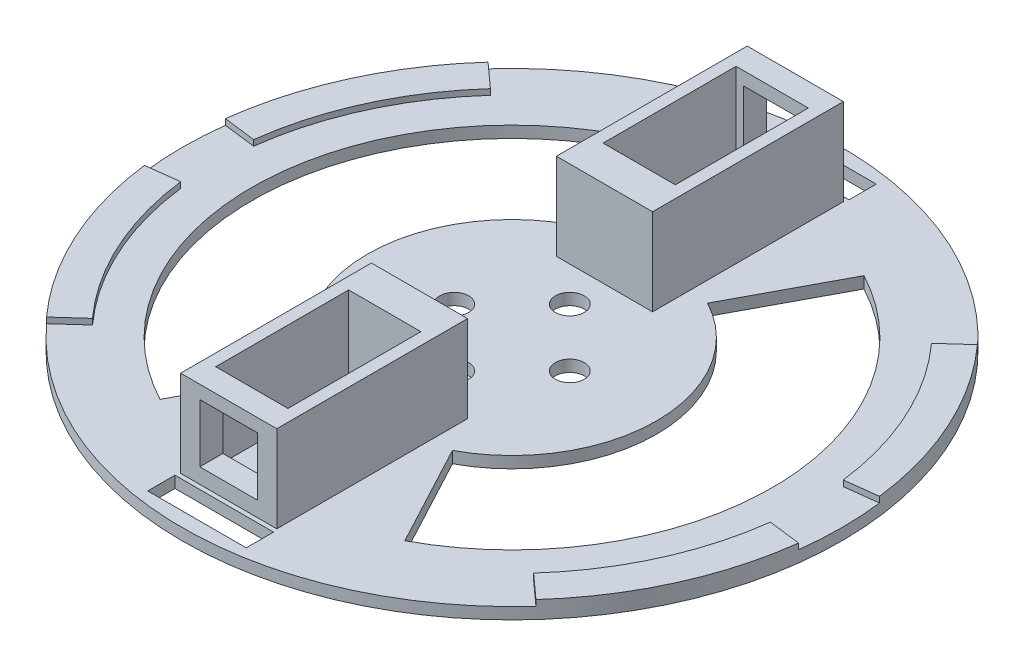
SolidWorks part; units mm, degrees
ref_plane "Front Plane" through (0, 0, 0) normal (0, 0, 1) x (1, 0, 0)
ref_plane "Top Plane" through (0, 0, 0) normal (0, 1, 0) x (1, 0, 0)
ref_plane "Right Plane" through (0, 0, 0) normal (1, 0, 0) x (0, 0, -1)
sketch "Sketch1" plane through (0, 0, 0) normal (0, 1, 0) x (1, 0, 0)
  circle A0 centre (0, 0) radius 57
  dimension "D1" = 114
extrude "Boss-Extrude1" add sketch "Sketch1" along normal blind 2
sketch "Sketch2" plane through (0, 2, 0) normal (0, 1, 0) x (1, 0, 0)
  line L0 (0, 57) -> (0, -57) construction
  line L1 (-57, 0) -> (57, 0) construction
  line L2 (-56.5685, 7) -> (-50.987, 6.3093)
  line L3 (-42.3232, 38.1804) -> (-38.1472, 34.4132)
  line L4 (42.3232, 38.1804) -> (38.1472, 34.4132)
  line L5 (56.5685, 7) -> (50.987, 6.3093)
  line L6 (56.5685, -7) -> (50.987, -6.3093)
  line L7 (42.3232, -38.1804) -> (38.1472, -34.4132)
  line L8 (-42.3232, -38.1804) -> (-38.1472, -34.4132)
  line L9 (-56.5685, -7) -> (-50.987, -6.3093)
  arc A0 (-38.1472, 34.4132) -> (-50.987, 6.3093) centre (0, 0) ccw
  circle A1 centre (0, 0) radius 57
  arc A2 (-42.3232, 38.1804) -> (-56.5685, 7) centre (0, 0) ccw
  arc A3 (38.1472, 34.4132) -> (50.987, 6.3093) centre (0, 0) cw
  arc A4 (42.3232, 38.1804) -> (56.5685, 7) centre (0, 0) cw
  arc A5 (42.3232, -38.1804) -> (56.5685, -7) centre (0, 0) ccw
  arc A6 (38.1472, -34.4132) -> (50.987, -6.3093) centre (0, 0) ccw
  arc A7 (-38.1472, -34.4132) -> (-50.987, -6.3093) centre (0, 0) cw
  arc A8 (-42.3232, -38.1804) -> (-56.5685, -7) centre (0, 0) cw
  dimension "D3" = 51.3759
  dimension "D2" = 35
  dimension "D4" = 7
  dimension "D1" = 0
extrude "Boss-Extrude2" add sketch "Sketch2" along normal blind 1
sketch "Sketch3" plane through (0, 2, 0) normal (0, 1, 0) x (1, 0, 0)
  line L0 (0, 64.138) -> (0, -67.5791) construction
  line L1 (-84.211, 0) -> (75.226, 0) construction
  line L2 (-18.0657, 32.5) -> (16.7275, 32.5) construction
  line L3 (-6.25, 45) -> (6.25, 45)
  line L4 (-6.25, 45) -> (-6.25, 22)
  line L5 (-6.25, 22) -> (6.25, 22)
  line L6 (6.25, 45) -> (6.25, 22)
  line L9 (-8.316, 49) -> (8.316, 49)
  line L10 (-8.316, 49) -> (-8.316, 16)
  line L11 (-8.316, 16) -> (8.316, 16)
  line L12 (8.316, 49) -> (8.316, 16)
  point P5 (0, 32.5)
  point P10 (0.6003, 32.4783)
  dimension "D1" = 23
  dimension "D2" = 12.5
  dimension "D3" = 22
  dimension "D4" = 49
  dimension "D5" = 16
extrude "Boss-Extrude3" add sketch "Sketch3" along normal blind 15
sketch "Sketch4" plane through (0, 0, -49) normal (0, 0, -1) x (-1, 0, 0)
  line L0 (0, 19.9695) -> (0, 2.7068) construction
  line L1 (-5, 14.7135) -> (5, 14.7135)
  line L2 (-5, 14.7135) -> (-5, 4.6291)
  line L3 (-5, 4.6291) -> (5, 4.6291)
  line L4 (5, 14.7135) -> (5, 4.6291)
  line L5 (-5, 14.7135) -> (5, 4.6291) construction
  line L6 (-5, 4.6291) -> (5, 14.7135) construction
  point P0 (0, 9.6713)
  dimension "D1" = 10
extrude "Cut-Extrude1" cut sketch "Sketch4" against normal blind 20
sketch "Sketch5" plane through (0, 2, 0) normal (0, 1, 0) x (1, 0, 0)
  line L0 (0, 66.6436) -> (0, 35.7965) construction
  line L2 (-8.5216, 54.4862) -> (8.5216, 54.4862)
  line L3 (-8.5216, 54.4862) -> (-8.5216, 49.7684)
  line L4 (-8.5216, 49.7684) -> (8.5216, 49.7684)
  line L5 (8.5216, 54.4862) -> (8.5216, 49.7684)
  line L6 (-8.5216, 54.4862) -> (8.5216, 49.7684) construction
  line L7 (-8.5216, 49.7684) -> (8.5216, 54.4862) construction
  point P3 (0, 52.1273)
extrude "Cut-Extrude2" cut sketch "Sketch5" against normal blind 20
mirror "Mirror1" about plane through (0, 0, 0) normal (0, 0, 1) of "Cut-Extrude2", "Cut-Extrude1", "Boss-Extrude3"
sketch "Sketch6" plane through (0, 2, 0) normal (0, 1, 0) x (1, 0, 0)
  line L0 (-78.3006, 0) -> (79.8937, 0) construction
  line L1 (0, 66.413) -> (0, -80.4067) construction
  line L2 (-21.1723, 39.7081) -> (-11.7624, 22.0601)
  line L3 (21.1723, 39.7081) -> (11.7624, 22.0601)
  line L4 (21.1723, -39.7081) -> (11.7624, -22.0601)
  line L5 (-21.1723, -39.7081) -> (-11.7624, -22.0601)
  circle A0 centre (-10, 0) radius 2.5
  circle A1 centre (0, 10) radius 2.5
  circle A2 centre (10, 0) radius 2.5
  circle A3 centre (0, -10) radius 2.5
  arc A4 (11.7624, -22.0601) -> (11.7624, 22.0601) centre (0, 0) ccw
  arc A5 (-21.1723, 39.7081) -> (-21.1723, -39.7081) centre (0, 0) ccw
  arc A6 (21.1723, -39.7081) -> (21.1723, 39.7081) centre (0, 0) ccw
  arc A7 (-11.7624, 22.0601) -> (-11.7624, -22.0601) centre (0, 0) ccw
  point P16 (0, 0)
  dimension "D1" = 5
  dimension "D4" = 90
  dimension "D5" = 50
  dimension "D2" = 10
  dimension "D3" = 4
extrude "Cut-Extrude3" cut sketch "Sketch6" against normal blind 20
